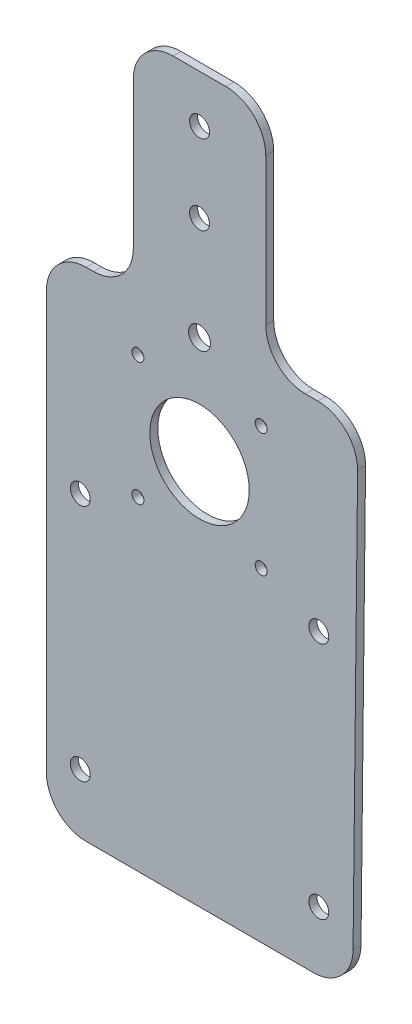
SolidWorks part; units mm, degrees
ref_plane "Front Plane" through (0, 0, 0) normal (0, 0, 1) x (1, 0, 0)
ref_plane "Top Plane" through (0, 0, 0) normal (0, 1, 0) x (1, 0, 0)
ref_plane "Right Plane" through (0, 0, 0) normal (1, 0, 0) x (0, 0, -1)
sketch "Sketch1" plane through (0, 0, 0) normal (0, 0, 1) x (1, 0, 0)
  line L1 (0, 0) -> (117, 0)
  line L2 (0, 0) -> (0, 200)
  line L3 (0, 200) -> (117, 200)
  line L4 (117, 0) -> (117, 200)
  dimension "D1" = 200
  dimension "D2" = 117
extrude "Boss-Extrude1" add sketch "Sketch1" along normal blind 2
sketch "Sketch2" plane through (0, 0, 2) normal (0, 0, 1) x (1, 0, 0)
  line L0 (0, 120) -> (117, 120) construction
  line L1 (0, 200) -> (0, 0) construction
  line L2 (117, 0) -> (117, 200) construction
  line L3 (0, 0) -> (117, 0) construction
  line L4 (0, 120) -> (40, 200)
  line L5 (117, 200) -> (0, 200) construction
  line L7 (77, 200) -> (117, 120)
  line L8 (40, 200) -> (0, 200)
  line L9 (0, 200) -> (0, 120)
  line L10 (77, 200) -> (117, 200)
  line L11 (117, 200) -> (117, 120)
  dimension "D1" = 120
  dimension "D2" = 40
  dimension "D3" = 40
extrude "Cut-Extrude1" cut sketch "Sketch2" against normal blind 2
sketch "Sketch3" plane through (0, 0, 2) normal (0, 0, 1) x (1, 0, 0)
  line L0 (58.5, 200) -> (58.5, 0) construction
  line L1 (77, 200) -> (40, 200) construction
  line L2 (0, 0) -> (117, 0) construction
  line L3 (0, 15) -> (117, 15) construction
  line L4 (48.5, 140) -> (68.5, 140) construction
  line L5 (48.5, 140) -> (48.5, 180) construction
  line L6 (48.5, 180) -> (68.5, 180) construction
  line L7 (68.5, 140) -> (68.5, 180) construction
  line L8 (48.5, 140) -> (68.5, 180) construction
  line L9 (48.5, 180) -> (68.5, 140) construction
  line L10 (0, 120) -> (0, 0) construction
  line L11 (117, 0) -> (117, 120) construction
  line L12 (0, 75) -> (117, 75) construction
  line L14 (36.5, 75) -> (80.5, 75) construction
  line L15 (36.5, 75) -> (36.5, 119) construction
  line L16 (36.5, 119) -> (80.5, 119) construction
  line L17 (80.5, 75) -> (80.5, 119) construction
  line L18 (36.5, 75) -> (80.5, 119) construction
  line L19 (36.5, 119) -> (80.5, 75) construction
  line L24 (0, 25) -> (117, 25) construction
  line L25 (0, 25) -> (0, 65) construction
  line L26 (0, 65) -> (117, 65) construction
  line L27 (117, 25) -> (117, 65) construction
  line L28 (0, 25) -> (117, 65) construction
  line L29 (0, 65) -> (117, 25) construction
  line L34 (43, 81.5) -> (74, 112.5) construction
  line L35 (43, 112.5) -> (74, 81.5) construction
  line L36 (68.25, 140) -> (48.75, 140) construction
  line L37 (68.25, 140) -> (68.25, 112) construction
  line L38 (68.25, 112) -> (48.75, 112) construction
  line L39 (48.75, 140) -> (48.75, 112) construction
  circle A0 centre (58.5, 170) radius 2.5
  circle A1 centre (58.5, 150) radius 2.5
  circle A2 centre (28.5, 15) radius 2.5
  circle A3 centre (88.5, 15) radius 2.5
  circle A4 centre (28.5, 75) radius 2.5
  circle A5 centre (88.5, 75) radius 2.5
  circle A6 centre (43, 112.5) radius 1.5
  circle A7 centre (43, 81.5) radius 1.5
  circle A8 centre (74, 81.5) radius 1.5
  circle A9 centre (74, 112.5) radius 1.5
  circle A10 centre (58.5, 97) radius 12.5
  circle A11 centre (58.5, 124) radius 2.75
  point P6 (58.5, 160)
  point P19 (58.5, 97)
  point P28 (58.5, 45)
  point P29 (58.5, 45)
  point P42 (58.5, 97)
  dimension "D6" = 5
  dimension "D7" = 5
  dimension "D14" = 5
  dimension "D15" = 5
  dimension "D16" = 5
  dimension "D17" = 5
  dimension "D22" = 3
  dimension "D23" = 3
  dimension "D24" = 3
  dimension "D25" = 3
  dimension "D31" = 25
  dimension "D35" = 5.5
  dimension "D1" = 20
  dimension "D2" = 40
  dimension "D3" = 20
  dimension "D4" = 20
  dimension "D5" = 10
  dimension "D8" = 40
  dimension "D9" = 10
  dimension "D10" = 15
  dimension "D11" = 10
  dimension "D12" = 60
  dimension "D13" = 30
  dimension "D18" = 60
  dimension "D19" = 30
  dimension "D20" = 44
  dimension "D21" = 44
  dimension "D26" = 0
  dimension "D27" = 31
  dimension "D28" = 31
  dimension "D29" = 31
  dimension "D30" = 15.5
  dimension "D32" = 19.5
  dimension "D33" = 28
  dimension "D34" = 9.75
  dimension "D36" = 12
extrude "Cut-Extrude2" cut sketch "Sketch3" against normal blind 30 contours A10 | A6 | A9 | A8 | A7 | A4 | A5 | A3 | A2 | A0 | A1 | A11
fillet "Fillet1" radius 20 6 edges at (40, 200, 1) (77, 200, 1) (117, 120, 1) (0, 120, 1) (0, 0, 1) (117, 0, 1)
sketch "Sketch4" plane through (0, 0, 0) normal (0, 0, -1) x (-1, 0, 0)
  line L0 (-97, 0) -> (-98.7082, 156.5836)
  line L1 (-82.5279, 188.9443) -> (-114.8885, 124.2229) construction
  line L3 (-2.1115, 124.2229) -> (-34.4721, 188.9443) construction
  line L4 (-20, 0) -> (-20, 160)
  line L5 (-20, 160) -> (-18.2918, 156.5836)
  line L10 (-2.1115, 124.2229) -> (-34.4721, 188.9443)
  line L11 (-52.3607, 200) -> (-64.6393, 200)
  line L12 (-82.5279, 188.9443) -> (-114.8885, 124.2229)
  line L13 (-117, 115.2786) -> (-117, 20)
  line L14 (-97, 0) -> (-20, 0)
  line L15 (0, 20) -> (0, 115.2786)
  line L16 (-2.1115, 124.2229) -> (-18.2918, 156.5836)
  line L18 (-98.7082, 156.5836) -> (-114.8885, 124.2229)
  line L19 (-117, 115.2786) -> (-117, 20)
  line L21 (0, 20) -> (0, 115.2786)
  arc A0 (-20, 0) -> (0, 20) centre (-20, 20) ccw construction
  arc A7 (-34.4721, 188.9443) -> (-52.3607, 200) centre (-52.3607, 180) ccw
  arc A8 (-64.6393, 200) -> (-82.5279, 188.9443) centre (-64.6393, 180) ccw
  arc A9 (-114.8885, 124.2229) -> (-117, 115.2786) centre (-97, 115.2786) ccw
  arc A10 (-117, 20) -> (-97, 0) centre (-97, 20) ccw
  arc A11 (-20, 0) -> (0, 20) centre (-20, 20) ccw
  arc A12 (0, 115.2786) -> (-2.1115, 124.2229) centre (-20, 115.2786) ccw
  arc A15 (-114.8885, 124.2229) -> (-117, 115.2786) centre (-97, 115.2786) ccw
  arc A16 (-117, 20) -> (-97, 0) centre (-97, 20) ccw
  arc A17 (-20, 0) -> (0, 20) centre (-20, 20) ccw
  arc A18 (0, 115.2786) -> (-2.1115, 124.2229) centre (-20, 115.2786) ccw
  dimension "D1" = 0
extrude "Cut-Extrude3" cut sketch "Sketch4" against normal blind 10
fillet "Fillet2" radius 10 4 edges at (20, 160, 1) (20, 0, 1) (97, 0, 1) (98.7082, 156.5836, 1)
sketch "Sketch5" plane through (0, 0, 0) normal (0, 0, -1) x (-1, 0, 0)
  line L0 (-75.1539, 197.013) -> (-75.1539, 125.0558)
  line L1 (-75.1539, 125.0558) -> (-98.3643, 125.0558)
  line L2 (-97.1079, 9.8909) -> (-98.6818, 154.1654) construction
  line L4 (-41.8461, 197.013) -> (-41.8461, 125.0558)
  line L5 (-41.8461, 125.0558) -> (-20, 125.0558)
  line L6 (-20, 157.6393) -> (-20, 10) construction
  line L13 (-20, 10) -> (-20, 157.6393)
  line L14 (-21.0557, 162.1115) -> (-34.4721, 188.9443)
  line L15 (-52.3607, 200) -> (-64.6393, 200)
  line L16 (-82.5279, 188.9443) -> (-97.6267, 158.7466)
  line L17 (-98.6818, 154.1654) -> (-97.1079, 9.8909)
  line L18 (-87.1085, 0) -> (-30, 0)
  line L19 (-20, 125.0558) -> (-20, 157.6393)
  line L20 (-21.0557, 162.1115) -> (-34.4721, 188.9443)
  line L22 (-82.5279, 188.9443) -> (-97.6267, 158.7466)
  line L23 (-98.6818, 154.1654) -> (-98.3643, 125.0558)
  arc A0 (-64.6393, 200) -> (-82.5279, 188.9443) centre (-64.6393, 180) ccw construction
  arc A2 (-34.4721, 188.9443) -> (-52.3607, 200) centre (-52.3607, 180) ccw construction
  arc A9 (-20, 157.6393) -> (-21.0557, 162.1115) centre (-30, 157.6393) ccw
  arc A10 (-34.4721, 188.9443) -> (-52.3607, 200) centre (-52.3607, 180) ccw
  arc A11 (-64.6393, 200) -> (-82.5279, 188.9443) centre (-64.6393, 180) ccw
  arc A12 (-97.6267, 158.7466) -> (-98.6818, 154.1654) centre (-88.6824, 154.2745) ccw
  arc A13 (-97.1079, 9.8909) -> (-87.1085, 0) centre (-87.1085, 10) ccw
  arc A14 (-30, 0) -> (-20, 10) centre (-30, 10) ccw
  arc A15 (-20, 157.6393) -> (-21.0557, 162.1115) centre (-30, 157.6393) ccw
  arc A16 (-34.4721, 188.9443) -> (-41.8461, 197.013) centre (-52.3607, 180) ccw
  arc A17 (-75.1539, 197.013) -> (-82.5279, 188.9443) centre (-64.6393, 180) ccw
  arc A18 (-97.6267, 158.7466) -> (-98.6818, 154.1654) centre (-88.6824, 154.2745) ccw
  dimension "D1" = 0
extrude "Cut-Extrude4" cut sketch "Sketch5" against normal blind 10
fillet "Fillet3" radius 10 6 edges at (75.1539, 197.013, 1) (41.8461, 197.013, 1) (41.8461, 125.0558, 1) (20, 125.0558, 1) (75.1539, 125.0558, 1) (98.3643, 125.0558, 1)
sketch "Sketch6" plane through (0, 0, 0) normal (0, 0, -1) x (-1, 0, 0)
  line L0 (-75.1539, 182) -> (-41.8461, 182)
  line L1 (-75.1539, 189.9867) -> (-75.1539, 135.0558) construction
  line L2 (-41.8461, 189.9867) -> (-41.8461, 135.0558) construction
  line L11 (-75.1539, 189.9867) -> (-75.1539, 135.0558)
  line L12 (-85.1539, 125.0558) -> (-88.2546, 125.0558)
  line L13 (-98.254, 114.9467) -> (-97.1079, 9.8909)
  line L14 (-87.1085, 0) -> (-30, 0)
  line L15 (-20, 10) -> (-20, 115.0558)
  line L16 (-30, 125.0558) -> (-31.8461, 125.0558)
  line L17 (-41.8461, 135.0558) -> (-41.8461, 189.9867)
  line L18 (-52.3607, 200) -> (-64.6393, 200)
  line L19 (-75.1539, 189.9867) -> (-75.1539, 182)
  line L20 (-85.1539, 125.0558) -> (-88.2546, 125.0558)
  line L25 (-41.8461, 182) -> (-41.8461, 189.9867)
  line L26 (-52.3607, 200) -> (-64.6393, 200)
  arc A10 (-64.6393, 200) -> (-65.6686, 199.9735) centre (-64.6393, 180) ccw
  arc A11 (-65.6686, 199.9735) -> (-75.1539, 189.9867) centre (-65.1539, 189.9867) ccw
  arc A12 (-85.1539, 125.0558) -> (-75.1539, 135.0558) centre (-85.1539, 135.0558) ccw
  arc A13 (-88.2546, 125.0558) -> (-98.254, 114.9467) centre (-88.2546, 115.0558) ccw
  arc A14 (-97.1079, 9.8909) -> (-87.1085, 0) centre (-87.1085, 10) ccw
  arc A15 (-30, 0) -> (-20, 10) centre (-30, 10) ccw
  arc A16 (-20, 115.0558) -> (-30, 125.0558) centre (-30, 115.0558) ccw
  arc A17 (-41.8461, 135.0558) -> (-31.8461, 125.0558) centre (-31.8461, 135.0558) ccw
  arc A18 (-41.8461, 189.9867) -> (-51.3314, 199.9735) centre (-51.8461, 189.9867) ccw
  arc A19 (-51.3314, 199.9735) -> (-52.3607, 200) centre (-52.3607, 180) ccw
  arc A20 (-64.6393, 200) -> (-65.6686, 199.9735) centre (-64.6393, 180) ccw
  arc A21 (-65.6686, 199.9735) -> (-75.1539, 189.9867) centre (-65.1539, 189.9867) ccw
  arc A28 (-41.8461, 189.9867) -> (-51.3314, 199.9735) centre (-51.8461, 189.9867) ccw
  arc A29 (-51.3314, 199.9735) -> (-52.3607, 200) centre (-52.3607, 180) ccw
  arc M32 (-64.6393, 200) -> (-65.6686, 199.9735) centre (-64.6393, 180) ccw
  arc M33 (-65.6686, 199.9735) -> (-75.1539, 189.9867) centre (-65.1539, 189.9867) ccw
  line M34 (-75.1539, 189.9867) -> (-75.1539, 135.0558)
  line M46 (-41.8461, 135.0558) -> (-41.8461, 189.9867)
  arc M47 (-41.8461, 189.9867) -> (-51.3314, 199.9735) centre (-51.8461, 189.9867) ccw
  arc M48 (-51.3314, 199.9735) -> (-52.3607, 200) centre (-52.3607, 180) ccw
  line M49 (-52.3607, 200) -> (-64.6393, 200)
  dimension "D2" = 18
  dimension "D1" = 0
extrude "Cut-Extrude5" cut sketch "Sketch6" against normal blind 10 contours L0 M34 M46 M47 M48 M49 M32 M33
fillet "Fillet4" radius 10 2 edges at (41.8461, 182, 1) (75.1539, 182, 1)
